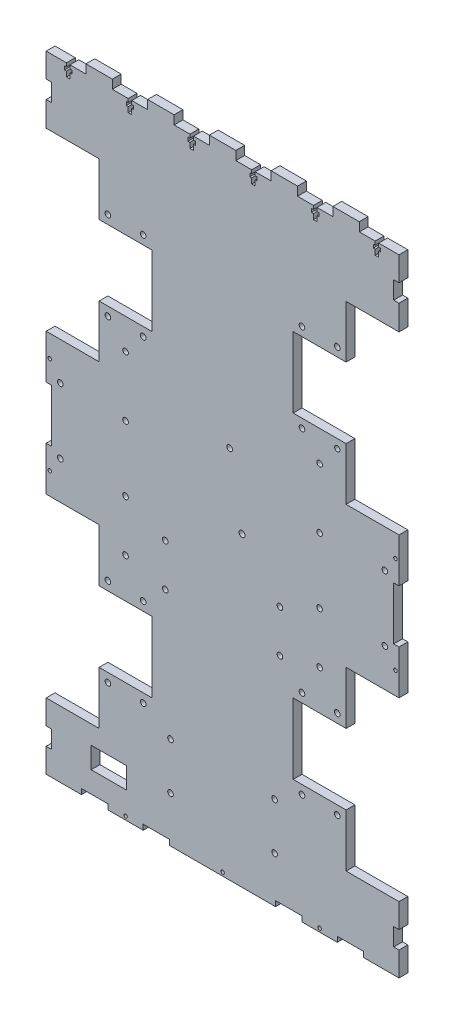
SolidWorks part; units mm, degrees
ref_plane "Front" through (0, 0, 0) normal (0, 0, 1) x (1, 0, 0)
ref_plane "Top" through (0, 0, 0) normal (0, 1, 0) x (1, 0, 0)
ref_plane "Right" through (0, 0, 0) normal (1, 0, 0) x (0, 0, -1)
sketch "四轮中心位置" plane through (0, 0, 0) normal (0, 0, 1) x (1, 0, 0)
  line L1 (0, 0) -> (180, 0)
  line L2 (0, 0) -> (0, 180)
  line L3 (0, 180) -> (180, 180)
  line L4 (180, 0) -> (180, 180)
  dimension "D1" = 180
  dimension "D2" = 180
sketch "四轮示意图" plane through (0, 0, 0) normal (0, 0, 1) x (1, 0, 0)
  line L1 (16, 137.5) -> (-16, 137.5)
  line L2 (16, 137.5) -> (16, 222.5)
  line L3 (16, 222.5) -> (-16, 222.5)
  line L4 (-16, 137.5) -> (-16, 222.5)
  line L5 (16, 137.5) -> (-16, 222.5) construction
  line L6 (16, 222.5) -> (-16, 137.5) construction
  line L7 (196, 137.5) -> (164, 137.5)
  line L8 (196, 137.5) -> (196, 222.5)
  line L9 (196, 222.5) -> (164, 222.5)
  line L10 (164, 137.5) -> (164, 222.5)
  line L11 (196, 137.5) -> (164, 222.5) construction
  line L12 (196, 222.5) -> (164, 137.5) construction
  line L13 (-16, -42.5) -> (16, -42.5)
  line L14 (-16, -42.5) -> (-16, 42.5)
  line L15 (-16, 42.5) -> (16, 42.5)
  line L16 (16, -42.5) -> (16, 42.5)
  line L17 (-16, -42.5) -> (16, 42.5) construction
  line L18 (-16, 42.5) -> (16, -42.5) construction
  line L19 (164, -42.5) -> (196, -42.5)
  line L20 (164, -42.5) -> (164, 42.5)
  line L21 (164, 42.5) -> (196, 42.5)
  line L22 (196, -42.5) -> (196, 42.5)
  line L23 (164, -42.5) -> (196, 42.5) construction
  line L24 (164, 42.5) -> (196, -42.5) construction
  point P0 (0, 180)
  point P5 (180, 180)
  point P11 (0, 0)
  point P17 (180, 0)
  dimension "D1" = 32
  dimension "D2" = 85
  dimension "D3" = 32
  dimension "D4" = 85
  dimension "D5" = 32
  dimension "D6" = 85
  dimension "D7" = 32
  dimension "D8" = 85
sketch "草图3" plane through (0, 0, 0) normal (0, 0, 1) x (1, 0, 0)
  line L0 (-10, 267.5) -> (190, 267.5)
  line L1 (190, 267.5) -> (190, 230)
  line L2 (190, 230) -> (160, 230)
  line L3 (160, 230) -> (160, 130)
  line L4 (160, 130) -> (190, 130)
  line L5 (190, 130) -> (190, 50)
  line L6 (190, 50) -> (160, 50)
  line L7 (160, 50) -> (160, -50)
  line L8 (160, -50) -> (190, -50)
  line L9 (190, -50) -> (190, -87.5)
  line L10 (190, -87.5) -> (-10, -87.5)
  line L11 (-10, -87.5) -> (-10, -50)
  line L12 (-10, -50) -> (20, -50)
  line L13 (20, -50) -> (20, 50)
  line L14 (20, 50) -> (-10, 50)
  line L15 (-10, 50) -> (-10, 130)
  line L16 (-10, 130) -> (20, 130)
  line L17 (20, 130) -> (20, 230)
  line L18 (20, 230) -> (-10, 230)
  line L19 (-10, 230) -> (-10, 267.5)
  line L20 (0, 0) -> (180, 0) construction
  line L21 (0, 0) -> (0, 180) construction
  point P22 (90, -87.5)
  point P23 (90, 0)
  point P24 (-10, 90)
  point P27 (0, 90)
  dimension "D1" = 200
  dimension "D2" = 355
  dimension "D3" = 100
  dimension "D4" = 100
  dimension "D5" = 100
  dimension "D6" = 100
  dimension "D7" = 30
  dimension "D8" = 30
  dimension "D9" = 30
  dimension "D10" = 30
  dimension "D11" = 80
  dimension "D12" = 37.5
  dimension "D13" = 80
  dimension "D14" = 37.5
  dimension "D15" = 30
  dimension "D16" = 30
  dimension "D17" = 0
  dimension "D18" = 0
  dimension "D19" = 200
  dimension "D20" = 0
extrude "凸台-拉伸1" add sketch "草图3" along normal blind 5
sketch "电机位置" plane through (0, 0, 5) normal (0, 0, 1) x (1, 0, 0)
  line L1 (33, 195) -> (57, 195)
  line L2 (33, 195) -> (33, 165)
  line L3 (33, 165) -> (57, 165)
  line L4 (57, 195) -> (57, 165)
  line L5 (33, 15) -> (57, 15)
  line L6 (33, 15) -> (33, -15)
  line L7 (33, -15) -> (57, -15)
  line L8 (57, 15) -> (57, -15)
  line L9 (123, 195) -> (147, 195)
  line L10 (123, 195) -> (123, 165)
  line L11 (123, 165) -> (147, 165)
  line L12 (147, 195) -> (147, 165)
  line L13 (123, 15) -> (147, 15)
  line L14 (123, 15) -> (123, -15)
  line L15 (123, -15) -> (147, -15)
  line L16 (147, 15) -> (147, -15)
  point P20 (57, 195)
  point P22 (33, 165)
  point P23 (57, 165)
  dimension "D1" = 24
  dimension "D2" = 30
  dimension "D3" = 33
  dimension "D4" = 15
  dimension "D5" = 24
  dimension "D6" = 30
  dimension "D7" = 33
  dimension "D8" = 15
  dimension "D9" = 24
  dimension "D10" = 30
  dimension "D11" = 33
  dimension "D12" = 15
  dimension "D13" = 24
  dimension "D14" = 30
  dimension "D15" = 15
  dimension "D16" = 33
sketch "草图5" plane through (0, 0, 5) normal (0, 0, 1) x (1, 0, 0)
  circle A0 centre (33, 195) radius 1.6
  circle A1 centre (57, 195) radius 1.6
  circle A2 centre (33, 165) radius 1.6
  circle A3 centre (57, 165) radius 1.6
  circle A4 centre (123, 195) radius 1.6
  circle A5 centre (147, 195) radius 1.6
  circle A6 centre (123, 165) radius 1.6
  circle A7 centre (147, 165) radius 1.6
  circle A8 centre (33, 15) radius 1.6
  circle A9 centre (57, 15) radius 1.6
  circle A10 centre (33, -15) radius 1.6
  circle A11 centre (57, -15) radius 1.6
  circle A12 centre (123, 15) radius 1.6
  circle A13 centre (147, 15) radius 1.6
  circle A14 centre (123, -15) radius 1.6
  circle A15 centre (147, -15) radius 1.6
  dimension "D1" = 3.2
  dimension "D2" = 3.2
extrude "切除-拉伸1" cut sketch "草图5" against normal through all
sketch "草图6" plane through (0, 0, 5) normal (0, 0, 1) x (1, 0, 0)
  line L0 (-10, 130) -> (-10, 50) construction
  line L1 (-10, 105) -> (-7, 105)
  line L2 (-10, 105) -> (-10, 75)
  line L3 (-10, 75) -> (-7, 75)
  line L4 (-7, 105) -> (-7, 75)
  line L5 (190, 50) -> (190, 130) construction
  line L7 (187, 105) -> (190, 105)
  line L8 (187, 105) -> (187, 75)
  line L9 (187, 75) -> (190, 75)
  line L10 (190, 105) -> (190, 75)
  point P6 (-7, 90)
  point P9 (190, 90)
  point P14 (190, 90)
  dimension "D1" = 30
  dimension "D2" = 3
  dimension "D3" = 0
  dimension "D4" = 3
  dimension "D5" = 30
  dimension "D6" = 0
  dimension "D7" = 0
extrude "切除-拉伸2" cut sketch "草图6" against normal through all
sketch "草图7" plane through (0, 0, 5) normal (0, 0, 1) x (1, 0, 0)
  line L0 (-10, 267.5) -> (-10, 230) construction
  line L1 (-10, 253.75) -> (-7, 253.75)
  line L2 (-10, 253.75) -> (-10, 243.75)
  line L3 (-10, 243.75) -> (-7, 243.75)
  line L4 (-7, 253.75) -> (-7, 243.75)
  line L5 (190, 230) -> (190, 267.5) construction
  line L6 (187, 253.75) -> (190, 253.75)
  line L7 (187, 253.75) -> (187, 243.75)
  line L8 (187, 243.75) -> (190, 243.75)
  line L9 (190, 253.75) -> (190, 243.75)
  line L10 (-10, -50) -> (-10, -87.5) construction
  line L11 (-10, -63.75) -> (-7, -63.75)
  line L12 (-10, -63.75) -> (-10, -73.75)
  line L13 (-10, -73.75) -> (-7, -73.75)
  line L14 (-7, -63.75) -> (-7, -73.75)
  line L15 (190, -87.5) -> (190, -50) construction
  line L16 (187, -63.75) -> (190, -63.75)
  line L17 (187, -63.75) -> (187, -73.75)
  line L18 (187, -73.75) -> (190, -73.75)
  line L19 (190, -63.75) -> (190, -73.75)
  point P4 (-10, 248.75)
  point P7 (-10, 248.75)
  point P12 (190, 248.75)
  point P15 (190, 248.75)
  point P20 (-10, -68.75)
  point P23 (-10, -68.75)
  point P28 (190, -68.75)
  point P31 (190, -68.75)
  dimension "D1" = 3
  dimension "D2" = 10
  dimension "D3" = 0
  dimension "D4" = 0
  dimension "D5" = 3
  dimension "D6" = 10
  dimension "D7" = 0
  dimension "D8" = 0
  dimension "D9" = 3
  dimension "D10" = 10
  dimension "D11" = 0
  dimension "D12" = 0
  dimension "D13" = 3
  dimension "D14" = 10
  dimension "D15" = 0
  dimension "D16" = 0
extrude "切除-拉伸3" cut sketch "草图7" against normal through all
sketch "草图8" plane through (0, 0, 5) normal (0, 0, 1) x (1, 0, 0)
  line L0 (-10, -87.5) -> (190, -87.5) construction
  line L1 (10, -87.5) -> (25, -87.5)
  line L2 (10, -87.5) -> (10, -84.5)
  line L3 (10, -84.5) -> (25, -84.5)
  line L4 (25, -87.5) -> (25, -84.5)
  line L6 (45, -87.5) -> (60, -87.5)
  line L7 (45, -87.5) -> (45, -84.5)
  line L8 (45, -84.5) -> (60, -84.5)
  line L9 (60, -87.5) -> (60, -84.5)
  line L10 (120, -87.5) -> (135, -87.5)
  line L11 (120, -87.5) -> (120, -84.5)
  line L12 (120, -84.5) -> (135, -84.5)
  line L13 (135, -87.5) -> (135, -84.5)
  line L14 (155, -87.5) -> (170, -87.5)
  line L15 (155, -87.5) -> (155, -84.5)
  line L16 (155, -84.5) -> (170, -84.5)
  line L17 (170, -87.5) -> (170, -84.5)
  point P10 (90, -87.5)
  dimension "D1" = 15
  dimension "D2" = 3
  dimension "D3" = 15
  dimension "D4" = 3
  dimension "D5" = 20
  dimension "D6" = 30
  dimension "D7" = 15
  dimension "D8" = 30
  dimension "D9" = 20
  dimension "D10" = 15
extrude "切除-拉伸4" cut sketch "草图8" against normal through all
sketch "草图9" plane through (0, 0, 5) normal (0, 0, 1) x (1, 0, 0)
  line L0 (20, 230) -> (20, 130) construction
  line L1 (-10, 230) -> (20, 230)
  line L2 (-10, 230) -> (-10, 229.64)
  line L3 (-10, 229.64) -> (20, 229.64)
  line L4 (20, 230) -> (20, 229.64)
  line L6 (160, 230) -> (190, 230)
  line L7 (160, 230) -> (160, 229.64)
  line L8 (160, 229.64) -> (190, 229.64)
  line L9 (190, 230) -> (190, 229.64)
  dimension "D1" = 0.36
  dimension "D2" = 0.36
extrude "凸台-拉伸2" add sketch "草图9" against normal blind 5
sketch "草图10" plane through (0, 0, 0) normal (0, 0, -1) x (-1, 0, 0)
  line L0 (-160, 130) -> (-160, 229.64) construction
  line L1 (-160, 199.82) -> (-130, 199.82)
  line L2 (-160, 199.82) -> (-160, 159.82)
  line L3 (-160, 159.82) -> (-130, 159.82)
  line L4 (-130, 199.82) -> (-130, 159.82)
  line L7 (-20, 229.64) -> (-20, 130) construction
  line L8 (-20, 50) -> (-20, -50) construction
  line L9 (-20, 199.82) -> (-50, 199.82)
  line L10 (-20, 199.82) -> (-20, 159.82)
  line L11 (-20, 159.82) -> (-50, 159.82)
  line L12 (-50, 199.82) -> (-50, 159.82)
  line L13 (-20, 20) -> (-50, 20)
  line L14 (-20, 20) -> (-20, -20)
  line L15 (-20, -20) -> (-50, -20)
  line L16 (-50, 20) -> (-50, -20)
  line L17 (-160, -50) -> (-160, 50) construction
  line L19 (-160, 20) -> (-130, 20)
  line L20 (-160, 20) -> (-160, -20)
  line L21 (-160, -20) -> (-130, -20)
  line L22 (-130, 20) -> (-130, -20)
  circle A1 centre (-25, 204.82) radius 1.6
  circle A4 centre (-25, 154.82) radius 1.6
  circle A5 centre (-25, 25) radius 1.6
  circle A7 centre (-25, -25) radius 1.6
  circle A10 centre (-155, 204.82) radius 1.6
  circle A11 centre (-155, 154.82) radius 1.5
  circle A14 centre (-155, 25) radius 1.6
  circle A16 centre (-155, -25) radius 1.6
  circle A17 centre (-135, 204.82) radius 1.6
  circle A18 centre (-135, 154.82) radius 1.6
  circle A19 centre (-135, 25) radius 1.6
  circle A20 centre (-45, 204.82) radius 1.6
  circle A21 centre (-45, 154.82) radius 1.6
  circle A22 centre (-45, 25) radius 1.6
  circle A23 centre (-45, -25) radius 1.6
  circle A24 centre (-135, -25) radius 1.6
  point P6 (-130, 179.82)
  point P9 (-20, 179.82)
  point P20 (-50, 0)
  point P23 (-160, 0)
  dimension "D4" = 30
  dimension "D7" = 5
  dimension "D8" = 5
  dimension "D12" = 5
  dimension "D13" = 5
  dimension "D15" = 5
  dimension "D24" = 20
  dimension "D25" = 20
  dimension "D1" = 30
  dimension "D2" = 40
  dimension "D3" = 0
  dimension "D5" = 40
  dimension "D6" = 0
  dimension "D9" = 0
  dimension "D18" = 30
  dimension "D21" = 30
extrude "电机固定板" cut sketch "草图10" against normal through all
sketch "草图11" plane through (0, 0, 0) normal (0, 0, -1) x (-1, 0, 0)
  line L1 (-50, 199.82) -> (-130, 199.82)
  line L2 (-50, 199.82) -> (-50, -20)
  line L3 (-50, -20) -> (-130, -20)
  line L4 (-130, 199.82) -> (-130, -20)
extrude "凸台-拉伸3" add sketch "草图11" against normal blind 5
sketch "草图12" plane through (0, 0, 0) normal (0, 0, -1) x (-1, 0, 0)
  line L0 (-190, 267.5) -> (10, 267.5) construction
  line L1 (-97.5, 267.5) -> (-82.5, 267.5)
  line L2 (-97.5, 267.5) -> (-97.5, 272.5)
  line L3 (-97.5, 272.5) -> (-82.5, 272.5)
  line L4 (-82.5, 267.5) -> (-82.5, 272.5)
  line L5 (-60, -87.5) -> (-120, -87.5) construction
  line L7 (-62.5, 267.5) -> (-47.5, 267.5)
  line L8 (-62.5, 267.5) -> (-62.5, 272.5)
  line L9 (-62.5, 272.5) -> (-47.5, 272.5)
  line L10 (-47.5, 267.5) -> (-47.5, 272.5)
  line L11 (-27.5, 267.5) -> (-12.5, 267.5)
  line L12 (-27.5, 267.5) -> (-27.5, 272.5)
  line L13 (-27.5, 272.5) -> (-12.5, 272.5)
  line L14 (-12.5, 267.5) -> (-12.5, 272.5)
  line L15 (-117.5, 267.5) -> (-132.5, 267.5)
  line L16 (-117.5, 267.5) -> (-117.5, 272.5)
  line L17 (-117.5, 272.5) -> (-132.5, 272.5)
  line L18 (-132.5, 267.5) -> (-132.5, 272.5)
  line L19 (-167.5, 267.5) -> (-152.5, 267.5)
  line L20 (-167.5, 267.5) -> (-167.5, 272.5)
  line L21 (-167.5, 272.5) -> (-152.5, 272.5)
  line L22 (-152.5, 267.5) -> (-152.5, 272.5)
  point P6 (-90, 272.5)
  point P9 (-90, -87.5)
  dimension "D1" = 15
  dimension "D2" = 5
  dimension "D3" = 0
  dimension "D4" = 15
  dimension "D5" = 20
  dimension "D6" = 15
  dimension "D7" = 20
  dimension "D8" = 15
  dimension "D9" = 20
  dimension "D10" = 20
  dimension "15" = 15
extrude "凸台-拉伸4" add sketch "草图12" against normal blind 5
sketch "草图13" plane through (0, 0, 0) normal (0, 0, -1) x (-1, 0, 0)
  line L0 (-152.5, 267.5) -> (-132.5, 267.5) construction
  line L1 (-143.5, 267.5) -> (-141.5, 267.5)
  line L2 (-143.5, 267.5) -> (-143.5, 265.5)
  line L3 (-143.5, 260.5) -> (-141.5, 260.5)
  line L4 (-141.5, 267.5) -> (-141.5, 265.5)
  line L5 (-141.5, 265.5) -> (-140.45, 265.5)
  line L6 (-144.55, 265.5) -> (-143.5, 265.5)
  line L7 (-144.55, 265.5) -> (-144.55, 263.5)
  line L8 (-144.55, 263.5) -> (-143.5, 263.5)
  line L9 (-140.45, 265.5) -> (-140.45, 263.5)
  line L10 (-143.5, 263.5) -> (-143.5, 260.5)
  line L11 (-141.5, 263.5) -> (-141.5, 260.5)
  line L12 (-141.5, 263.5) -> (-140.45, 263.5)
  point P10 (-142.5, 267.5)
  point P11 (-142.5, 267.5)
  dimension "D1" = 2
  dimension "D2" = 7
  dimension "D3" = 4.1
  dimension "D4" = 1.05
  dimension "D5" = 2
  dimension "D6" = 2
  dimension "D7" = 0
extrude "切除-拉伸6" cut sketch "草图13" against normal through all
pattern_linear "阵列(线性)1" count 5 spacing 35 along (-1, 0, 0) count 2 spacing 35 along (1, 0, 0) of "切除-拉伸6"
sketch "草图14" plane through (0, 0, 0) normal (0, 0, -1) x (-1, 0, 0)
  line L0 (-190, 105) -> (-190, 130) construction
  line L1 (-190, 118.5) -> (-188, 118.5)
  line L2 (-190, 118.5) -> (-190, 116.5)
  line L3 (-190, 116.5) -> (-188, 116.5)
  line L4 (-183, 118.5) -> (-183, 116.5)
  line L5 (-188, 119.55) -> (-186, 119.55)
  line L6 (-188, 119.55) -> (-188, 118.5)
  line L7 (-188, 115.45) -> (-186, 115.45)
  line L8 (-186, 119.55) -> (-186, 118.5)
  line L9 (-186, 118.5) -> (-183, 118.5)
  line L10 (-188, 116.5) -> (-188, 115.45)
  line L11 (-186, 116.5) -> (-186, 115.45)
  line L12 (-186, 116.5) -> (-183, 116.5)
  point P8 (-190, 117.5)
  point P11 (-190, 117.5)
  dimension "D1" = 7
  dimension "D2" = 2
  dimension "D3" = 2
  dimension "D4" = 4.1
  dimension "D5" = 1.05
  dimension "D6" = 2
  dimension "D7" = 0
  dimension "D8" = 0
sketch "草图15" plane through (0, 0, 5) normal (0, 0, 1) x (1, 0, 0)
  line L0 (60, -87.5) -> (120, -87.5) construction
  circle A0 centre (90, -85.5) radius 1
  circle A1 centre (145, -85.5) radius 1
  circle A2 centre (35, -85.5) radius 1
  point P4 (90, -87.5)
  dimension "D1" = 0
  dimension "D2" = 2
extrude "切除-拉伸8" cut sketch "草图15" against normal through all
sketch "草图16" plane through (0, 0, 5) normal (0, 0, 1) x (1, 0, 0)
  line L0 (190, 50) -> (190, 75) construction
  line L1 (-10, 75) -> (-10, 50) construction
  circle A0 centre (188, 62.5) radius 1
  circle A1 centre (188, 117.4035) radius 1
  circle A2 centre (-8, 62.5) radius 1
  circle A3 centre (-8, 117.5) radius 1
  point P4 (190, 62.5)
  dimension "D1" = 0
  dimension "D2" = 2
  dimension "D3" = 2
  dimension "D4" = 2
extrude "切除-拉伸9" cut sketch "草图16" against normal through all
sketch "主控位置限定" plane through (0, 0, 5) normal (0, 0, 1) x (1, 0, 0)
  line L0 (187, 105) -> (187, 75) construction
  line L1 (112.5, 70) -> (67.5, 70)
  line L2 (112.5, 70) -> (112.5, 130)
  line L3 (112.5, 130) -> (67.5, 130)
  line L4 (67.5, 70) -> (67.5, 130)
  line L5 (60, -87.5) -> (120, -87.5) construction
  point P4 (112.5, 100)
  point P7 (187, 90)
  point P8 (90, 70)
  point P11 (90, -87.5)
  dimension "D1" = 45
  dimension "D2" = 60
  dimension "D3" = 10
  dimension "D4" = 0
sketch "草图18" plane through (0, 0, 5) normal (0, 0, 1) x (1, 0, 0)
  line L4 (112.5, 70) -> (67.5, 70) construction
  line L5 (112.5, 70) -> (112.5, 130) construction
  circle A0 centre (94, 124.6) radius 1.6
  circle A1 centre (101, 86) radius 1.7
  dimension "D1" = 11.5
  dimension "D2" = 16
  dimension "D3" = 7
  dimension "D4" = 38.6
extrude "主控孔位" cut sketch "草图18" against normal through all
sketch "L298N限定" plane through (0, 0, 5) normal (0, 0, 1) x (1, 0, 0)
  line L0 (187, 105) -> (187, 75) construction
  line L1 (182, 71.5) -> (145, 71.5)
  line L2 (182, 71.5) -> (182, 108.5)
  line L3 (182, 108.5) -> (145, 108.5)
  line L4 (145, 71.5) -> (145, 108.5)
  line L5 (35, 71.5) -> (-2, 71.5)
  line L6 (35, 71.5) -> (35, 108.5)
  line L7 (35, 108.5) -> (-2, 108.5)
  line L8 (-2, 71.5) -> (-2, 108.5)
  line L9 (-7, 75) -> (-7, 105) construction
  point P8 (182, 90)
  point P11 (187, 90)
  point P12 (-2, 90)
  point P15 (-7, 90)
  dimension "D1" = 37
  dimension "D2" = 37
  dimension "D3" = 37
  dimension "D4" = 37
  dimension "D5" = 0
  dimension "D6" = 0
  dimension "D7" = 5
  dimension "D8" = 5
sketch "草图20" plane through (0, 0, 5) normal (0, 0, 1) x (1, 0, 0)
  circle A0 centre (182, 71.5) radius 1.6
  circle A1 centre (145, 108.5) radius 1.6
  circle A2 centre (145, 71.5) radius 1.6
  circle A3 centre (182, 108.5) radius 1.6
  circle A4 centre (35, 71.5) radius 1.6
  circle A5 centre (-2, 108.5) radius 1.6
  circle A6 centre (-2, 71.5) radius 1.6
  circle A7 centre (35, 108.5) radius 1.6
extrude "切除-拉伸11" cut sketch "草图20" against normal through all
sketch "陀螺仪固定位置" plane through (0, 0, 5) normal (0, 0, 1) x (1, 0, 0)
  line L0 (187, 105) -> (187, 75) construction
  line L1 (98, 82) -> (82, 82)
  line L2 (98, 82) -> (98, 98)
  line L3 (98, 98) -> (82, 98)
  line L4 (82, 82) -> (82, 98)
  line L5 (60, -87.5) -> (120, -87.5) construction
  point P6 (98, 90)
  point P7 (187, 90)
  point P8 (90, 82)
  point P11 (90, -87.5)
  dimension "D1" = 16
  dimension "D2" = 16
  dimension "D3" = 0
  dimension "D4" = 0
sketch "电源稳压模块限定" plane through (0, 0, 5) normal (0, 0, 1) x (1, 0, 0)
  line L0 (82.5, 272.5) -> (97.5, 272.5) construction
  line L1 (119.5, -61.5) -> (60.5, -61.5)
  line L2 (119.5, -61.5) -> (119.5, -35)
  line L3 (119.5, -35) -> (60.5, -35)
  line L4 (60.5, -61.5) -> (60.5, -35)
  circle A1 centre (135, -25) radius 1.6 construction
  point P4 (90, -35)
  point P7 (90, 272.5)
  dimension "D1" = 59
  dimension "D2" = 26.5
  dimension "D3" = 0
  dimension "D4" = 10
sketch "草图23" plane through (0, 0, 5) normal (0, 0, 1) x (1, 0, 0)
  circle A0 centre (119.5, -61.5) radius 1.6
  circle A1 centre (60.5, -61.5) radius 1.6
  circle A2 centre (119.5, -35) radius 1.6
  circle A3 centre (60.5, -35) radius 1.6
extrude "稳压模块固定孔位" cut sketch "草图23" against normal through all
sketch "分电板位置限制" plane through (0, 0, 5) normal (0, 0, 1) x (1, 0, 0)
  line L0 (82.5, 272.5) -> (97.5, 272.5) construction
  line L1 (122.5, 37) -> (57.5, 37)
  line L2 (122.5, 37) -> (122.5, 61)
  line L3 (122.5, 61) -> (57.5, 61)
  line L4 (57.5, 37) -> (57.5, 61)
  circle A1 centre (135, 25) radius 1.6 construction
  point P4 (90, 61)
  point P7 (90, 272.5)
  dimension "D1" = 65
  dimension "D2" = 24
  dimension "D3" = 0
  dimension "D4" = 12
sketch "草图25" plane through (0, 0, 5) normal (0, 0, 1) x (1, 0, 0)
  circle A0 centre (122.5, 37) radius 1.6
  circle A1 centre (57.5, 37) radius 1.6
  circle A2 centre (122.5, 61) radius 1.6
  circle A3 centre (57.5, 61) radius 1.6
extrude "分电板孔位" cut sketch "草图25" against normal through all
sketch "草图26" plane through (0, 0, 5) normal (0, 0, 1) x (1, 0, 0)
  line L0 (160, 20) -> (160, 50) construction
  line L2 (20, 229.64) -> (20, 199.82) construction
  line L4 (12.5, 272.5) -> (27.5, 272.5) construction
  line L5 (135, -87.5) -> (155, -87.5) construction
  circle A0 centre (145, 42.5) radius 1.6
  circle A1 centre (35, 142.5) radius 1.6
  circle A2 centre (145, 142.5) radius 1.6
  circle A3 centre (35, 42.5) radius 1.6
  dimension "D1" = 15
  dimension "D2" = 130
  dimension "D3" = 15
  dimension "D4" = 130
  dimension "D5" = 0
  dimension "D6" = 0
extrude "电池固定孔位" cut sketch "草图26" against normal through all
sketch "草图27" plane through (0, 0, 5) normal (0, 0, 1) x (1, 0, 0)
  line L1 (35.5, -72.5) -> (15.5, -72.5)
  line L2 (35.5, -72.5) -> (35.5, -60.5)
  line L3 (35.5, -60.5) -> (15.5, -60.5)
  line L4 (15.5, -72.5) -> (15.5, -60.5)
  line L5 (170, -87.5) -> (190, -87.5) construction
  circle A0 centre (60.5, -35) radius 1.6 construction
  dimension "D1" = 20
  dimension "D2" = 12
  dimension "D3" = 25
  dimension "D4" = 15
extrude "开关位置" cut sketch "草图27" against normal through all
